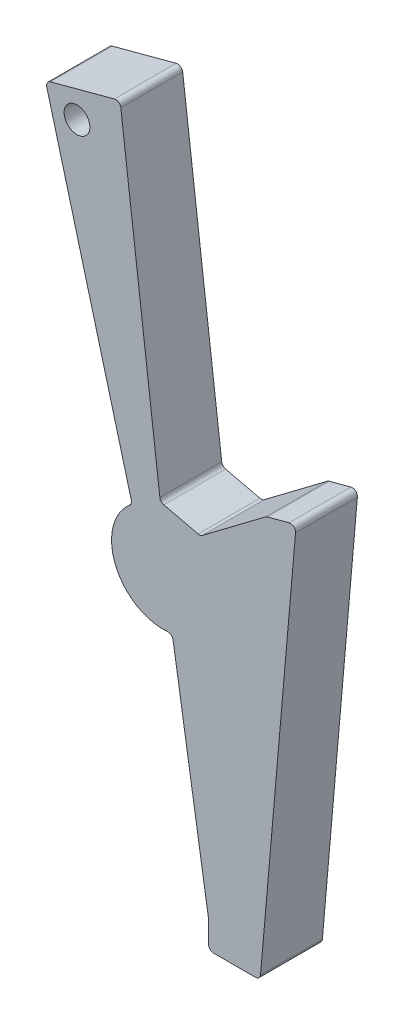
SolidWorks part; units mm, degrees
ref_plane "Front Plane" through (0, 0, 0) normal (0, 0, 1) x (1, 0, 0)
ref_plane "Top Plane" through (0, 0, 0) normal (0, 1, 0) x (1, 0, 0)
ref_plane "Right Plane" through (0, 0, 0) normal (1, 0, 0) x (0, 0, -1)
sketch "Sketch1" plane through (0, 0, 0) normal (0, 0, 1) x (1, 0, 0)
  line L0 (-23.8897, 0) -> (23.8897, 0) construction
  line L1 (0, -19.2687) -> (0, 19.2687) construction
  line L2 (0, 0) -> (-14.4889, -3.8823)
  line L3 (-14.4889, -3.8823) -> (2.3344, -66.6675)
  line L4 (0, 0) -> (7.7996, -63.523)
  line L5 (7.7996, -63.523) -> (15.5853, -65.3624)
  line L6 (15.5853, -65.3624) -> (28.3635, -55.7334)
  line L7 (28.3635, -55.7334) -> (34.159, -54.1805)
  line L8 (34.159, -54.1805) -> (27.1599, -134.1805)
  line L9 (27.1599, -134.1805) -> (17.1599, -134.1805)
  line L10 (17.1599, -134.1805) -> (17.1599, -128.9488)
  line L11 (17.1599, -128.9488) -> (10.1204, -84.5029)
  arc A0 (10.1204, -84.5029) -> (2.3344, -66.6675) centre (8.3411, -74.6624) cw
  point P4 (0, 0)
  point P8 (0, 0)
  dimension "D10" = 10
  dimension "D1" = 15
  dimension "D2" = 15
  dimension "D3" = 64
  dimension "D4" = 82
  dimension "D5" = 65
  dimension "D6" = 8
  dimension "D7" = 16
  dimension "D8" = 6
  dimension "D9" = 80
  dimension "D11" = 5.2317
  dimension "D12" = 45
  dimension "D13" = 10
  dimension "D14" = 95
  dimension "D15" = 9
  dimension "D16" = 110.293
  dimension "D17" = 60
extrude "Boss-Extrude1" add sketch "Sketch1" along normal blind 12
sketch "Sketch2" plane through (0, 0, 12) normal (0, 0, 1) x (1, 0, 0)
  line L0 (-14.4889, -3.8823) -> (2.3344, -66.6675) construction
  line L1 (0, 0) -> (-14.4889, -3.8823) construction
  circle A0 centre (-8.3652, -7.4178) radius 2.5
  point P2 (0, 0)
  point P3 (-7.6657, -8.3954)
  dimension "D1" = 5
  dimension "D2" = 5
  dimension "D3" = 5
extrude "Cut-Extrude1" cut sketch "Sketch2" against normal through all
fillet "Fillet1" radius 1 10 edges at (-14.4889, -3.8823, 6) (0, 0, 6) (15.5853, -65.3624, 6) (7.7996, -63.523, 6) (28.3635, -55.7334, 6) (34.159, -54.1805, 6) (17.1599, -134.1805, 6) (27.1599, -134.1805, 6) (2.3344, -66.6675, 6) (10.1204, -84.5029, 6)
